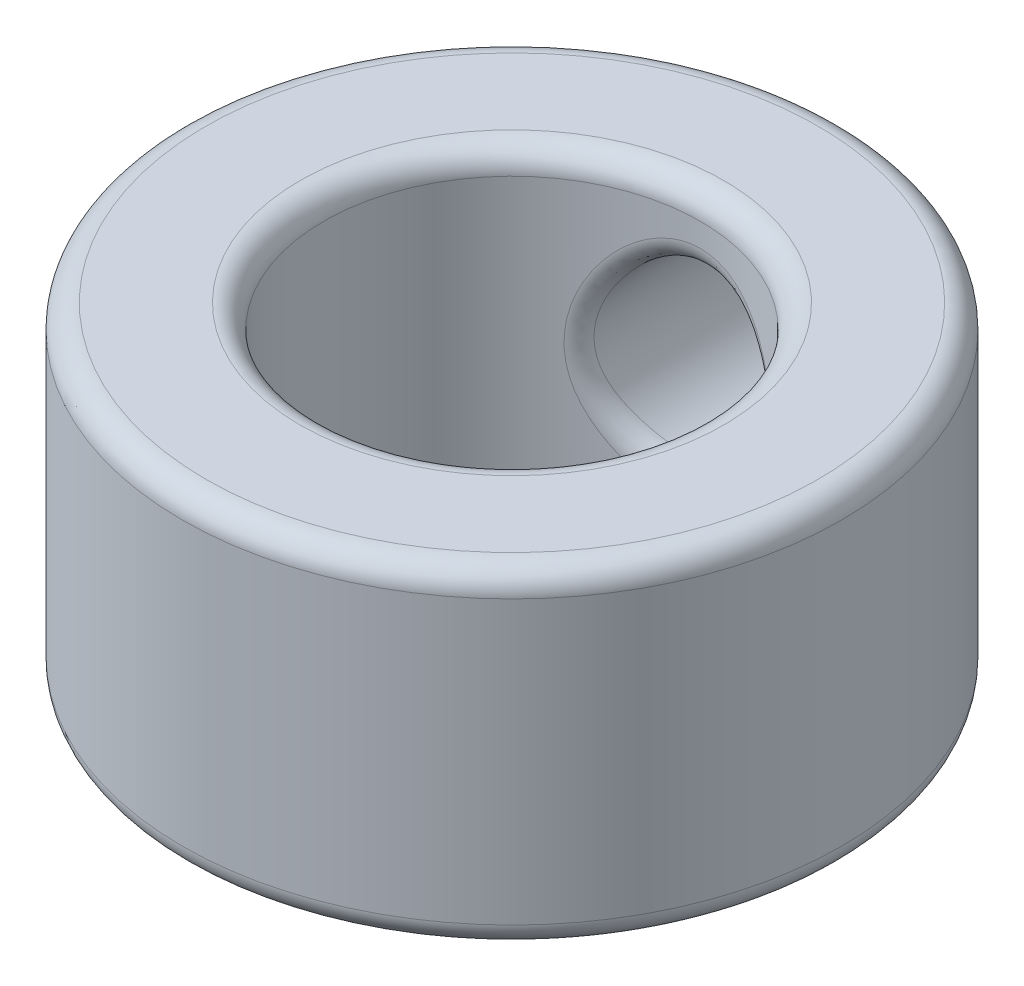
SolidWorks part; units mm, degrees
ref_plane "Front Plane" through (0, 0, 0) normal (0, 0, 1) x (1, 0, 0)
ref_plane "Top Plane" through (0, 0, 0) normal (0, 1, 0) x (1, 0, 0)
ref_plane "Right Plane" through (0, 0, 0) normal (1, 0, 0) x (0, 0, -1)
sketch "Sketch1" plane through (0, 0, 0) normal (0, 1, 0) x (1, 0, 0)
  circle A0 centre (0, 0) radius 7
  circle A1 centre (0, 0) radius 4
  dimension "D1" = 14
  dimension "D2" = 8
extrude "Boss-Extrude1" add sketch "Sketch1" along normal blind 7
sketch "Sketch2" plane through (0, 0, 0) normal (0, 0, 1) x (1, 0, 0)
  circle A0 centre (0, 3.5) radius 2
  dimension "D1" = 4
  dimension "D2" = 3.5
extrude "Cut-Extrude1" cut sketch "Sketch2" against normal up to next
fillet "Fillet1" radius 0.5 2 edges at (0, 0, 7) (0, 7, 7)
fillet "Fillet2" radius 0.5 3 edges at (0, 0, 4) (0, 7, 4) (-1.9886, 3.7136, -3.4707)
